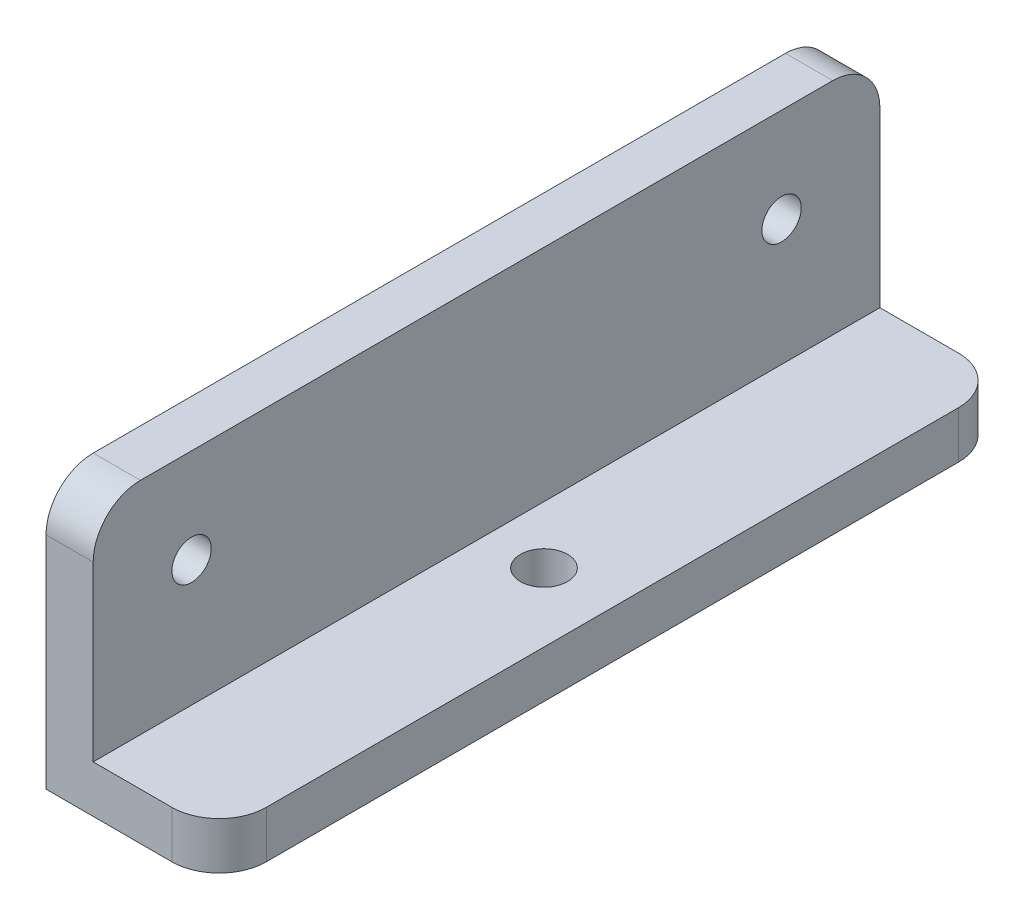
SolidWorks part; units mm, degrees
ref_plane "Front Plane" through (0, 0, 0) normal (0, 0, 1) x (1, 0, 0)
ref_plane "Top Plane" through (0, 0, 0) normal (0, 1, 0) x (1, 0, 0)
ref_plane "Right Plane" through (0, 0, 0) normal (1, 0, 0) x (0, 0, -1)
sketch "Sketch1" plane through (0, 0, 0) normal (0, 0, 1) x (1, 0, 0)
  line L0 (0, 34) -> (0, 0)
  line L1 (0, 0) -> (22, 0)
  line L2 (22, 0) -> (22, 6)
  line L3 (22, 6) -> (6, 6)
  line L4 (6, 6) -> (6, 34)
  line L5 (6, 34) -> (0, 34)
  dimension "D1" = 6
  dimension "D2" = 22
  dimension "D3" = 28
extrude "Boss-Extrude1" add sketch "Sketch1" along normal mid plane 100
sketch "Sketch2" plane through (6, 0, 0) normal (1, 0, 0) x (0, 0, -1)
  line L0 (0, 55) -> (0, -55) construction
  line L2 (-50, 0) -> (50, 0) construction
  circle A0 centre (-37.5, 22) radius 2.5
  circle A1 centre (37.5, 22) radius 2.5
  dimension "D3" = 5
  dimension "D1" = 75
  dimension "D2" = 22
extrude "Cut-Extrude1" cut sketch "Sketch2" against normal up to next
sketch "Sketch3" plane through (0, 6, 0) normal (0, 1, 0) x (1, 0, 0)
  line L0 (22, -50) -> (22, 50) construction
  circle A0 centre (13.3, 0) radius 3
  point P4 (22, 0)
  dimension "D1" = 6
  dimension "D2" = 8.7
extrude "Cut-Extrude2" cut sketch "Sketch3" against normal up to next
fillet "Fillet1" radius 6 4 edges at (22, 3, -50) (3, 34, -50) (3, 34, 50) (22, 3, 50)
